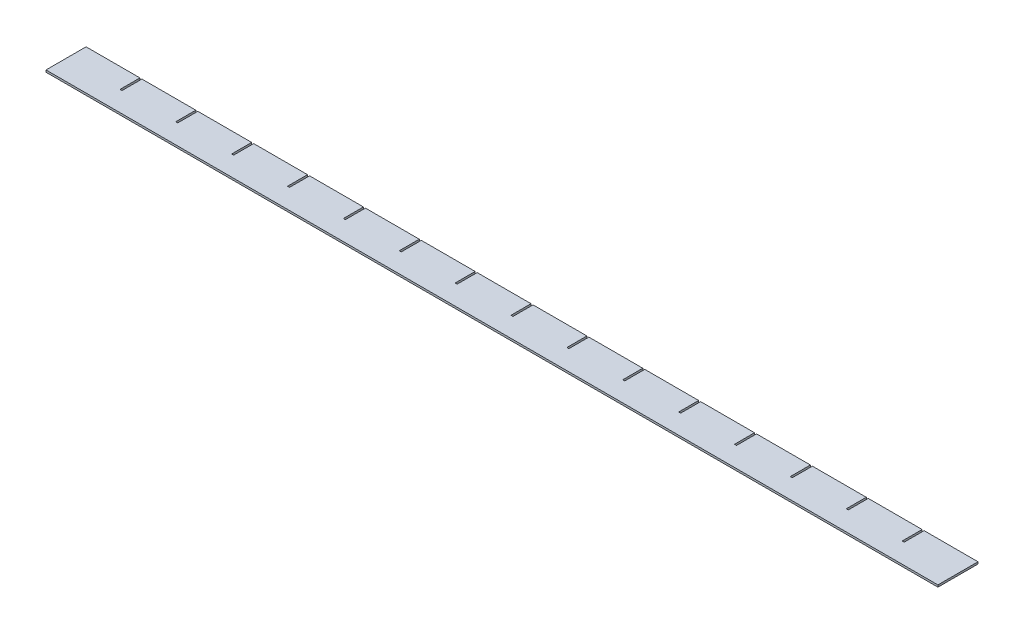
SolidWorks part; units mm, degrees
ref_plane "Front Plane" through (0, 0, 0) normal (0, 0, 1) x (1, 0, 0)
ref_plane "Top Plane" through (0, 0, 0) normal (0, 1, 0) x (1, 0, 0)
ref_plane "Right Plane" through (0, 0, 0) normal (1, 0, 0) x (0, 0, -1)
sketch "Sketch1" plane through (0, 0, 0) normal (0, 1, 0) x (1, 0, 0)
  line L1 (0, 0) -> (222.6, 0)
  line L2 (0, 0) -> (0, 10)
  line L3 (0, 10) -> (222.6, 10)
  line L4 (222.6, 0) -> (222.6, 10)
  dimension "D1" = 10
  dimension "D2" = 222.6
extrude "Boss-Extrude1" add sketch "Sketch1" along normal blind 0.5
sketch "Sketch2" plane through (0, 0.5, 0) normal (0, 1, 0) x (1, 0, 0)
  line L0 (222.6, 10) -> (0, 10) construction
  line L1 (13.4438, 10) -> (13.9437, 10)
  line L2 (13.4438, 10) -> (13.4437, 5)
  line L3 (13.4437, 5) -> (13.9437, 5)
  line L4 (13.9437, 10) -> (13.9437, 5)
  line L5 (0, 10) -> (0, 0) construction
  line L6 (0, 0) -> (222.6, 0) construction
  line L7 (27.3875, 10) -> (27.3875, 5)
  line L8 (27.8875, 10) -> (27.8875, 5)
  line L9 (27.3875, 10) -> (27.8875, 10)
  line L10 (27.3875, 5) -> (27.8875, 5)
  line L11 (41.3312, 10) -> (41.3312, 5)
  line L12 (41.8312, 10) -> (41.8312, 5)
  line L13 (41.3312, 10) -> (41.8312, 10)
  line L14 (41.3312, 5) -> (41.8312, 5)
  line L15 (55.275, 10) -> (55.275, 5)
  line L16 (55.775, 10) -> (55.775, 5)
  line L17 (55.275, 10) -> (55.775, 10)
  line L18 (55.275, 5) -> (55.775, 5)
  line L19 (69.2188, 10) -> (69.2188, 5)
  line L20 (69.7188, 10) -> (69.7188, 5)
  line L21 (69.2188, 10) -> (69.7188, 10)
  line L22 (69.2188, 5) -> (69.7188, 5)
  line L23 (83.1625, 10) -> (83.1625, 5)
  line L24 (83.6625, 10) -> (83.6625, 5)
  line L25 (83.1625, 10) -> (83.6625, 10)
  line L26 (83.1625, 5) -> (83.6625, 5)
  line L27 (97.1063, 10) -> (97.1063, 5)
  line L28 (97.6063, 10) -> (97.6063, 5)
  line L29 (97.1063, 10) -> (97.6063, 10)
  line L30 (97.1063, 5) -> (97.6063, 5)
  line L31 (111.05, 10) -> (111.05, 5)
  line L32 (111.55, 10) -> (111.55, 5)
  line L33 (111.05, 10) -> (111.55, 10)
  line L34 (111.05, 5) -> (111.55, 5)
  line L35 (124.9938, 10) -> (124.9938, 5)
  line L36 (125.4937, 10) -> (125.4937, 5)
  line L37 (124.9938, 10) -> (125.4937, 10)
  line L38 (124.9938, 5) -> (125.4937, 5)
  line L39 (138.9375, 10) -> (138.9375, 5)
  line L40 (139.4375, 10) -> (139.4375, 5)
  line L41 (138.9375, 10) -> (139.4375, 10)
  line L42 (138.9375, 5) -> (139.4375, 5)
  line L43 (152.8812, 10) -> (152.8812, 5)
  line L44 (153.3812, 10) -> (153.3812, 5)
  line L45 (152.8812, 10) -> (153.3812, 10)
  line L46 (152.8812, 5) -> (153.3812, 5)
  line L47 (166.825, 10) -> (166.825, 5)
  line L48 (167.325, 10) -> (167.325, 5)
  line L49 (166.825, 10) -> (167.325, 10)
  line L50 (166.825, 5) -> (167.325, 5)
  line L51 (180.7688, 10) -> (180.7688, 5)
  line L52 (181.2688, 10) -> (181.2688, 5)
  line L53 (180.7688, 10) -> (181.2688, 10)
  line L54 (180.7688, 5) -> (181.2688, 5)
  line L55 (194.7125, 10) -> (194.7125, 5)
  line L56 (195.2125, 10) -> (195.2125, 5)
  line L57 (194.7125, 10) -> (195.2125, 10)
  line L58 (194.7125, 5) -> (195.2125, 5)
  line L59 (208.6562, 10) -> (208.6562, 5)
  line L60 (209.1562, 10) -> (209.1562, 5)
  line L61 (208.6562, 10) -> (209.1562, 10)
  line L62 (208.6562, 5) -> (209.1562, 5)
  dimension "D1" = 13.4437
  dimension "D2" = 0.5
  dimension "D3" = 5
  dimension "D5" = 13.4437
  dimension "D6" = 5
  dimension "D4" = 15
extrude "Cut-Extrude1" cut sketch "Sketch2" against normal blind 0.5
equation "\"D5@Sketch2\"=\"D1@Sketch2\""
